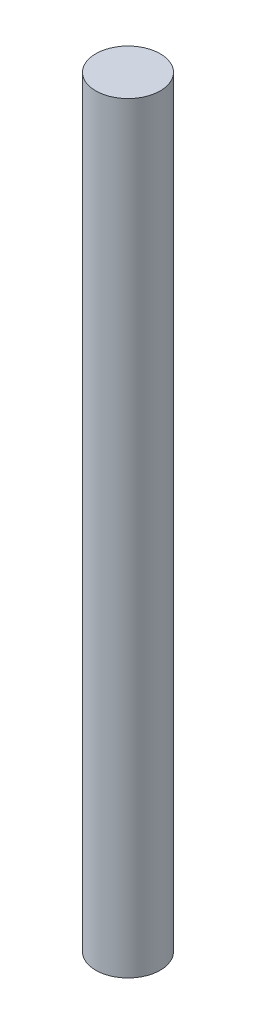
SolidWorks part; units mm, degrees
ref_plane "Front Plane" through (0, 0, 0) normal (0, 0, 1) x (1, 0, 0)
ref_plane "Top Plane" through (0, 0, 0) normal (0, 1, 0) x (1, 0, 0)
ref_plane "Right Plane" through (0, 0, 0) normal (1, 0, 0) x (0, 0, -1)
sketch "Sketch1" plane through (0, 0, 0) normal (0, 1, 0) x (1, 0, 0)
  circle A0 centre (0, 0) radius 22.5
  dimension "D1" = 45
extrude "Boss-Extrude1" add sketch "Sketch1" along normal blind 532
